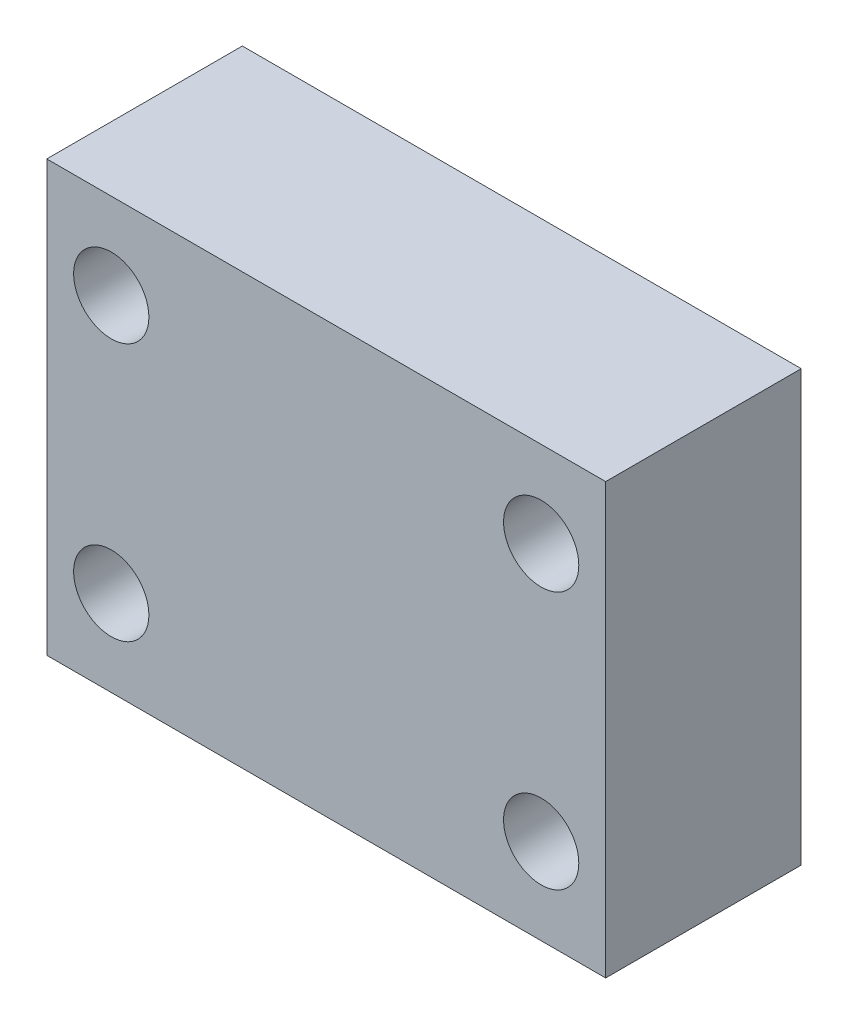
SolidWorks part; units mm, degrees
ref_plane "Front Plane" through (0, 0, 0) normal (0, 0, 1) x (1, 0, 0)
ref_plane "Top Plane" through (0, 0, 0) normal (0, 1, 0) x (1, 0, 0)
ref_plane "Right Plane" through (0, 0, 0) normal (1, 0, 0) x (0, 0, -1)
sketch "Sketch1" plane through (0, 0, 0) normal (0, 0, 1) x (1, 0, 0)
  line L1 (0, 0) -> (52, 0)
  line L2 (0, 0) -> (0, -40)
  line L3 (0, -40) -> (52, -40)
  line L4 (52, 0) -> (52, -40)
  circle A0 centre (6, -8) radius 3.5
  circle A1 centre (46, -8) radius 3.5
  circle A2 centre (6, -32) radius 3.5
  circle A3 centre (46, -32) radius 3.5
  dimension "D3" = 8
  dimension "D11" = 7
  dimension "D12" = 7
  dimension "D13" = 7
  dimension "D14" = 7
  dimension "D1" = 40
  dimension "D2" = 52
  dimension "D4" = 6
  dimension "D5" = 8
  dimension "D6" = 6
  dimension "D7" = 6
  dimension "D8" = 8
  dimension "D9" = 6
  dimension "D10" = 8
extrude "Boss-Extrude1" add sketch "Sketch1" along normal blind 18.1949
